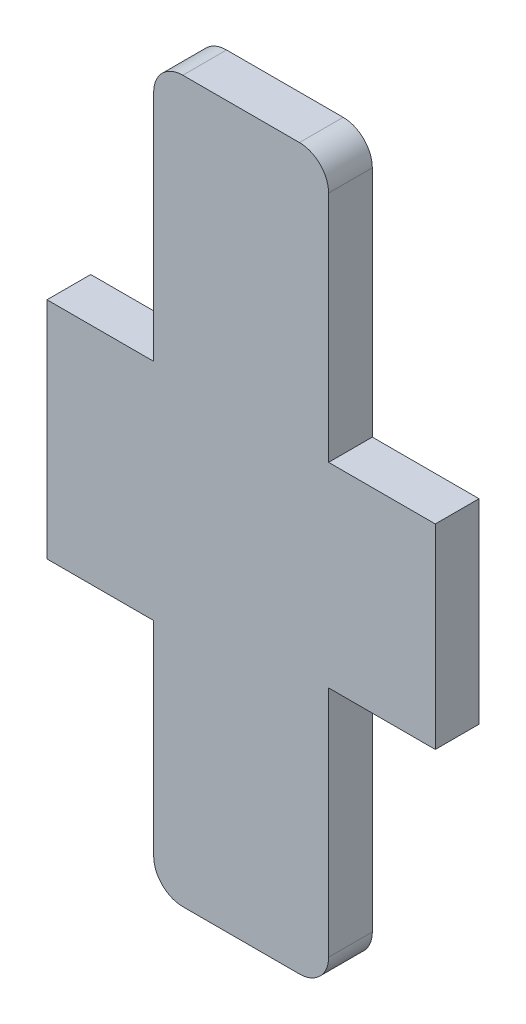
SolidWorks part; units mm, degrees
ref_plane "Front" through (0, 0, 0) normal (0, 0, 1) x (1, 0, 0)
ref_plane "Top" through (0, 0, 0) normal (0, 1, 0) x (1, 0, 0)
ref_plane "Right" through (0, 0, 0) normal (1, 0, 0) x (0, 0, -1)
sketch "Sketch1" plane through (0, 0, 0) normal (0, 0, 1) x (1, 0, 0)
  line L0 (-1588.3293, -37.3659) -> (-1588.3293, -51.3659)
  line L1 (-1576.3293, -51.3659) -> (-1576.3293, -35.3659)
  line L2 (-1595.649, -21.9659) -> (-1595.649, -37.3659)
  line L3 (-1595.649, -37.3659) -> (-1588.3293, -37.3659)
  line L5 (-1576.3293, -5.9659) -> (-1576.3293, -21.9659)
  line L6 (-1588.3293, -21.9659) -> (-1588.3293, -5.9659)
  line L7 (-1569.0097, -21.9659) -> (-1569.0097, -35.3659)
  line L9 (-1576.3293, -35.3659) -> (-1569.0097, -35.3659)
  line L11 (-1576.3293, -21.9659) -> (-1569.0097, -21.9659)
  line L12 (-1595.649, -21.9659) -> (-1588.3293, -21.9659)
  line L13 (-1586.3293, -3.9659) -> (-1578.3293, -3.9659)
  line L14 (-1586.3293, -53.3659) -> (-1578.3293, -53.3659)
  arc A0 (-1588.3293, -5.9659) -> (-1586.3293, -3.9659) centre (-1586.3293, -5.9659) cw
  arc A1 (-1576.3293, -5.9659) -> (-1578.3293, -3.9659) centre (-1578.3293, -5.9659) ccw
  arc A2 (-1578.3293, -53.3659) -> (-1576.3293, -51.3659) centre (-1578.3293, -51.3659) ccw
  arc A3 (-1586.3293, -53.3659) -> (-1588.3293, -51.3659) centre (-1586.3293, -51.3659) cw
  dimension "D2" = 2
  dimension "D1" = 18
  dimension "D3" = 12
  dimension "D6" = 90
  dimension "D8" = 90
extrude "Base-Extrude" add sketch "Sketch1" along normal blind 3
